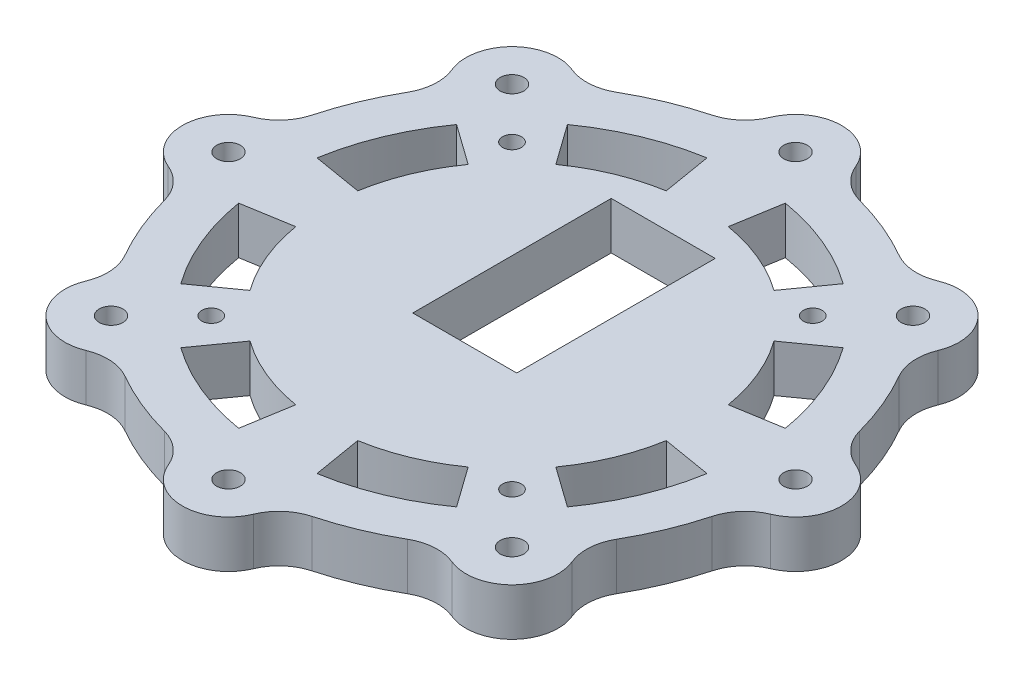
SolidWorks part; units mm, degrees
ref_plane "Alzado" through (0, 0, 0) normal (0, 0, 1) x (1, 0, 0)
ref_plane "Planta" through (0, 0, 0) normal (0, 1, 0) x (1, 0, 0)
ref_plane "Vista lateral" through (0, 0, 0) normal (1, 0, 0) x (0, 0, -1)
sketch "Croquis1" plane through (0, 0, 0) normal (0, 1, 0) x (1, 0, 0)
  line L0 (0, 0) -> (0, 75) construction
  line L1 (0, 0) -> (8.2936, 49.5609)
  line L2 (0, 0) -> (-8.2936, 49.5609)
  line L3 (0, 0) -> (40.9093, 29.1803)
  line L4 (0, 0) -> (29.1803, 40.9093)
  line L5 (0, 0) -> (49.5609, -8.2936)
  line L6 (0, 0) -> (49.5609, 8.2936)
  line L7 (0, 0) -> (29.1803, -40.9093)
  line L8 (0, 0) -> (40.9093, -29.1803)
  line L9 (0, 0) -> (-8.2936, -49.5609)
  line L10 (0, 0) -> (8.2936, -49.5609)
  line L11 (0, 0) -> (-40.9093, -29.1803)
  line L12 (0, 0) -> (-29.1803, -40.9093)
  line L13 (0, 0) -> (-49.5609, 8.2936)
  line L14 (0, 0) -> (-49.5609, -8.2936)
  line L15 (0, 0) -> (-29.1803, 40.9093)
  line L16 (0, 0) -> (-40.9093, 29.1803)
  line L17 (0, 0) -> (0, -82.5226) construction
  line L18 (-11, 32) -> (11, 32)
  line L19 (-11, 32) -> (-11, -10)
  line L20 (-11, -10) -> (11, -10)
  line L21 (11, 32) -> (11, -10)
  line L22 (-11, 32) -> (11, -10) construction
  line L23 (-11, -10) -> (11, 32) construction
  line L24 (0, 0) -> (42.4264, 42.4264) construction
  circle A1 centre (0, 0) radius 50.25
  circle A2 centre (0, 0) radius 39.75
  circle A3 centre (0, -60) radius 2.5
  circle A4 centre (-42.4264, -42.4264) radius 2.5
  circle A5 centre (-60, 0) radius 2.5
  circle A6 centre (-42.4264, 42.4264) radius 2.5
  circle A7 centre (0, 60) radius 2.5
  circle A8 centre (42.4264, 42.4264) radius 2.5
  circle A9 centre (60, 0) radius 2.5
  circle A10 centre (42.4264, -42.4264) radius 2.5
  circle A11 centre (31.8198, 31.8198) radius 2
  circle A12 centre (31.8198, -31.8198) radius 2
  circle A13 centre (-31.8198, -31.8198) radius 2
  circle A14 centre (-31.8198, 31.8198) radius 2
  circle A15 centre (0, 0) radius 60
  circle A16 centre (0, -60) radius 9.75
  circle A17 centre (-42.4264, -42.4264) radius 9.75
  circle A18 centre (-60, 0) radius 9.75
  circle A19 centre (-42.4264, 42.4264) radius 9.75
  circle A20 centre (0, 60) radius 9.75
  circle A21 centre (42.4264, 42.4264) radius 9.75
  circle A22 centre (60, 0) radius 9.75
  circle A23 centre (42.4264, -42.4264) radius 9.75
  point P5 (0, 11)
  point P25 (0, 0)
  point P48 (0, 0)
  point P57 (0, 0)
  point P74 (0, 0)
  dimension "D2" = 100.5
  dimension "D3" = 79.5
  dimension "D10" = 5
  dimension "D14" = 4
  dimension "D17" = 120
  dimension "D18" = 8
  dimension "D4" = 9.5
  dimension "D5" = 9.5
  dimension "D7" = 42
  dimension "D8" = 22
  dimension "D9" = 10
  dimension "D11" = 60
  dimension "D13" = 45
  dimension "D15" = 45
  dimension "D6" = 8
  dimension "D12" = 8
  dimension "D16" = 4
extrude "Saliente-Extruir1" add sketch "Croquis1" along normal blind 10
fillet "Redondeo1" radius 10 16 edges at (34.9947, 5, -48.7377) (48.7377, 5, -34.9947) (59.2078, 5, -9.7178) (59.2078, 5, 9.7178) (48.7377, 5, 34.9947) (34.9947, 5, 48.7377) (9.7178, 5, 59.2078) (-9.7178, 5, 59.2078) (-34.9947, 5, 48.7377) (-48.7377, 5, 34.9947) (-59.2078, 5, 9.7178) (-59.2078, 5, -9.7178) (-48.7377, 5, -34.9947) (-34.9947, 5, -48.7377) (-9.7178, 5, -59.2078) (9.7178, 5, -59.2078)
sketch "Croquis2" plane through (0, 0, 0) normal (0, -1, 0) x (1, 0, 0)
  circle A0 centre (31.8198, 31.8198) radius 5
  circle A1 centre (31.8198, -31.8198) radius 5
  circle A2 centre (-31.8198, -31.8198) radius 5
  circle A3 centre (-31.8198, 31.8198) radius 5
  point P13 (0, 0)
  dimension "D1" = 10
  dimension "D2" = 4
extrude "Cortar-Extruir1" cut sketch "Croquis2" against normal blind 5
